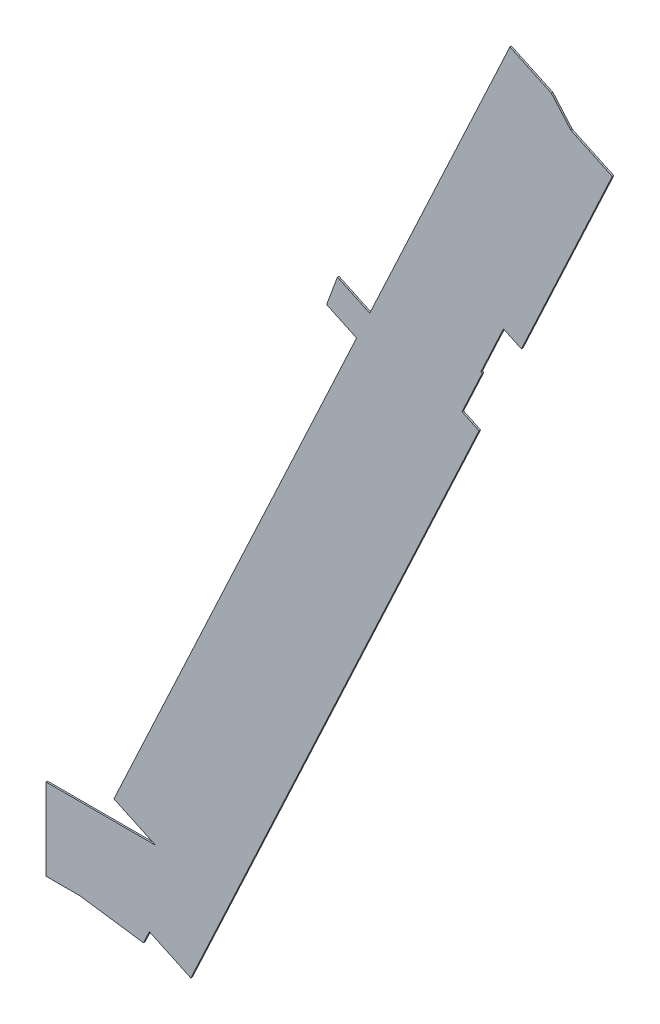
SolidWorks part; units mm, degrees
ref_plane "前视基准面" through (0, 0, 0) normal (0, 0, 1) x (1, 0, 0)
ref_plane "上视基准面" through (0, 0, 0) normal (0, 1, 0) x (1, 0, 0)
ref_plane "右视基准面" through (0, 0, 0) normal (1, 0, 0) x (0, 0, -1)
ref_plane "基准面4"
sketch "草图1" plane through (0, 0, 49.5) normal (0, 0, 1) x (1, 0, 0)
  line L0 (1395.4872, -638.5196) -> (1368.2979, -625.8411)
  line L1 (1368.2979, -625.8411) -> (1364.6212, -633.726)
  line L2 (1364.6212, -633.726) -> (1391.8104, -646.4045)
  line L3 (1391.8104, -646.4045) -> (1395.4872, -638.5196)
  line L4 (1345.9654, -713.9589) -> (1330.5581, -706.7744)
  line L5 (1330.5581, -706.7744) -> (1315.7665, -738.4951)
  line L6 (1315.7665, -738.4951) -> (1331.1737, -745.6797)
  line L7 (1331.1737, -745.6797) -> (1345.9654, -713.9589)
  line L8 (1406.3907, -615.1369) -> (1379.2015, -602.4583)
  line L9 (1379.2015, -602.4583) -> (1368.2979, -625.8411)
  line L10 (1368.2979, -625.8411) -> (1395.4872, -638.5196)
  line L11 (1395.4872, -638.5196) -> (1406.3907, -615.1369)
  line L12 (1176.9999, -1107.779) -> (1149.8106, -1095.1004)
  line L13 (1149.8106, -1095.1004) -> (1135.3148, -1126.1868)
  line L14 (1135.3148, -1126.1868) -> (1162.5041, -1138.8653)
  line L15 (1162.5041, -1138.8653) -> (1176.9999, -1107.779)
  line L16 (1207.7242, -1041.8904) -> (1180.535, -1029.2118)
  line L17 (1180.535, -1029.2118) -> (1165.4053, -1061.6577)
  line L18 (1165.4053, -1061.6577) -> (1192.5945, -1074.3362)
  line L19 (1192.5945, -1074.3362) -> (1207.7242, -1041.8904)
  line L20 (1238.4063, -976.0924) -> (1211.2171, -963.4139)
  line L21 (1211.2171, -963.4139) -> (1195.876, -996.3129)
  line L22 (1195.876, -996.3129) -> (1223.0653, -1008.9914)
  line L23 (1223.0653, -1008.9914) -> (1238.4063, -976.0924)
  line L24 (1223.0653, -1008.9914) -> (1195.876, -996.3129)
  line L25 (1195.876, -996.3129) -> (1180.535, -1029.2118)
  line L26 (1180.535, -1029.2118) -> (1207.7242, -1041.8904)
  line L27 (1207.7242, -1041.8904) -> (1223.0653, -1008.9914)
  line L28 (1192.5945, -1074.3362) -> (1165.4053, -1061.6577)
  line L29 (1165.4053, -1061.6577) -> (1149.8106, -1095.1004)
  line L30 (1149.8106, -1095.1004) -> (1176.9999, -1107.779)
  line L31 (1176.9999, -1107.779) -> (1192.5945, -1074.3362)
  line L32 (1391.8104, -646.4045) -> (1364.6212, -633.726)
  line L33 (1364.6212, -633.726) -> (1347.97, -669.4345)
  line L34 (1347.97, -669.4345) -> (1375.1592, -682.113)
  line L35 (1375.1592, -682.113) -> (1391.8104, -646.4045)
  line L36 (1375.1592, -682.113) -> (1347.97, -669.4345)
  line L37 (1347.97, -669.4345) -> (1330.5581, -706.7744)
  line L38 (1330.5581, -706.7744) -> (1345.9654, -713.9589)
  line L39 (1345.9654, -713.9589) -> (1357.7474, -719.4529)
  line L40 (1357.7474, -719.4529) -> (1375.1592, -682.113)
  line L41 (1113.8458, -1172.2272) -> (1141.0351, -1184.9058)
  line L42 (1141.0351, -1184.9058) -> (1162.5041, -1138.8653)
  line L43 (1162.5041, -1138.8653) -> (1135.3148, -1126.1868)
  line L44 (1135.3148, -1126.1868) -> (1113.8458, -1172.2272)
  line L45 (1305.8562, -831.4457) -> (1278.6669, -818.7672)
  line L46 (1278.6669, -818.7672) -> (1256.564, -866.1671)
  line L47 (1256.564, -866.1671) -> (1283.7532, -878.8456)
  line L48 (1283.7532, -878.8456) -> (1305.8562, -831.4457)
  line L49 (1283.7532, -878.8456) -> (1256.564, -866.1671)
  line L50 (1256.564, -866.1671) -> (1234.2498, -914.0201)
  line L51 (1234.2498, -914.0201) -> (1261.439, -926.6987)
  line L52 (1261.439, -926.6987) -> (1283.7532, -878.8456)
  line L53 (1261.439, -926.6987) -> (1234.2498, -914.0201)
  line L54 (1234.2498, -914.0201) -> (1211.2171, -963.4139)
  line L55 (1211.2171, -963.4139) -> (1238.4063, -976.0924)
  line L56 (1238.4063, -976.0924) -> (1261.439, -926.6987)
  line L57 (1318.7853, -774.6129) -> (1302.7444, -767.1329)
  line L58 (1302.7444, -767.1329) -> (1278.6669, -818.7672)
  line L59 (1278.6669, -818.7672) -> (1305.8562, -831.4457)
  line L60 (1305.8562, -831.4457) -> (1329.9336, -779.8115)
  line L61 (1329.9336, -779.8115) -> (1318.7853, -774.6129)
  line L62 (1226.4, -727) -> (1213.4, -757.7)
  line L63 (1213.4, -757.7) -> (1226.7468, -764.5456)
  line L64 (1226.7468, -764.5456) -> (1230.0392, -758.1265)
  line L65 (1230.0392, -758.1265) -> (1249.6843, -767.2872)
  line L66 (1249.6843, -767.2872) -> (1224.7498, -820.7594)
  line L67 (1224.7498, -820.7594) -> (1213.6349, -844.5953)
  line L68 (1213.6349, -844.5953) -> (1198.4207, -877.2223)
  line L69 (1198.4207, -877.2223) -> (1183.1219, -910.0307)
  line L70 (1183.1219, -910.0307) -> (1170.2743, -937.5824)
  line L71 (1170.2743, -937.5824) -> (1150.6648, -979.6351)
  line L72 (1150.6648, -979.6351) -> (1135.4506, -1012.2622)
  line L73 (1135.4506, -1012.2622) -> (1122.3494, -1040.3577)
  line L74 (1122.3494, -1040.3577) -> (1107.8959, -1071.3535)
  line L75 (1107.8959, -1071.3535) -> (1090.6108, -1108.4215)
  line L76 (1090.6108, -1108.4215) -> (1117.8, -1121.1)
  line L77 (1117.8, -1121.1) -> (1068.2, -1121.1)
  line L78 (1068.2, -1121.1) -> (1046.2, -1121.1)
  line L79 (1046.2, -1121.1) -> (1046.2, -1174.6)
  line L80 (1046.2, -1174.6) -> (1068.2, -1174.6)
  line L81 (1068.2, -1174.6) -> (1110, -1180.4746)
  line L82 (1110, -1180.4746) -> (1113.8458, -1172.2272)
  line L83 (1113.8458, -1172.2272) -> (1135.3148, -1126.1868)
  line L84 (1135.3148, -1126.1868) -> (1149.8106, -1095.1004)
  line L85 (1149.8106, -1095.1004) -> (1165.4053, -1061.6577)
  line L86 (1165.4053, -1061.6577) -> (1180.535, -1029.2118)
  line L87 (1180.535, -1029.2118) -> (1195.876, -996.3129)
  line L88 (1195.876, -996.3129) -> (1211.2171, -963.4139)
  line L89 (1211.2171, -963.4139) -> (1234.2498, -914.0201)
  line L90 (1234.2498, -914.0201) -> (1256.564, -866.1671)
  line L91 (1256.564, -866.1671) -> (1278.6669, -818.7672)
  line L92 (1278.6669, -818.7672) -> (1302.7444, -767.1329)
  line L93 (1302.7444, -767.1329) -> (1318.7853, -774.6129)
  line L94 (1318.7853, -774.6129) -> (1332.08, -746.1023)
  line L95 (1332.08, -746.1023) -> (1331.1737, -745.6797)
  line L96 (1331.1737, -745.6797) -> (1315.7665, -738.4951)
  line L97 (1315.7665, -738.4951) -> (1330.5581, -706.7744)
  line L98 (1330.5581, -706.7744) -> (1347.97, -669.4345)
  line L99 (1347.97, -669.4345) -> (1364.6212, -633.726)
  line L100 (1364.6212, -633.726) -> (1368.2979, -625.8411)
  line L101 (1368.2979, -625.8411) -> (1379.2015, -602.4583)
  line L102 (1379.2015, -602.4583) -> (1390.1051, -579.0756)
  line L103 (1390.1051, -579.0756) -> (1377.3775, -564.4342)
  line L104 (1377.3775, -564.4342) -> (1350.1883, -551.7557)
  line L105 (1350.1883, -551.7557) -> (1325.0425, -605.681)
  line L106 (1325.0425, -605.681) -> (1321.3657, -613.5659)
  line L107 (1321.3657, -613.5659) -> (1304.2497, -650.2714)
  line L108 (1304.2497, -650.2714) -> (1289.458, -681.9921)
  line L109 (1289.458, -681.9921) -> (1274.4973, -714.0754)
  line L110 (1274.4973, -714.0754) -> (1258.2688, -748.8776)
  line L111 (1258.2688, -748.8776) -> (1237.0998, -739.0064)
  line L112 (1237.0998, -739.0064) -> (1239.7468, -733.8456)
  line L113 (1239.7468, -733.8456) -> (1226.4, -727)
  line L114 (1390.1051, -579.0756) -> (1379.2015, -602.4583)
  line L115 (1379.2015, -602.4583) -> (1406.3907, -615.1369)
  line L116 (1406.3907, -615.1369) -> (1417.2943, -591.7542)
  line L117 (1417.2943, -591.7542) -> (1390.1051, -579.0756)
  dimension "D1" = 15
  dimension "D2" = 15
  dimension "D3" = 5.8
  dimension "D4" = 22
  dimension "D5" = 172
  dimension "D6" = 42.2108
  dimension "D7" = 49.6
  dimension "D8" = 107
  dimension "D9" = 9.1
  dimension "D10" = 30
  dimension "D11" = 50.8
  dimension "D12" = 34.3
  dimension "D13" = 36.9
  dimension "D14" = 35.8
  dimension "D15" = 36.3
  dimension "D16" = 36.3
  dimension "D17" = 54.5
  dimension "D18" = 52.8
  dimension "D19" = 52.3
  dimension "D20" = 30
  dimension "D21" = 40.9
  dimension "D22" = 34.2
  dimension "D23" = 31
  dimension "D24" = 36
  dimension "D25" = 46.4
  dimension "D26" = 30.4
  dimension "D27" = 36.2
  dimension "D28" = 36
  dimension "D29" = 26.3
  dimension "D30" = 59
  dimension "D31" = 38.4
  dimension "D32" = 35.4
  dimension "D33" = 35
  dimension "D34" = 40.5
  dimension "D35" = 8.7
  dimension "D36" = 59.5
  dimension "D37" = 30
  dimension "D38" = 90
  dimension "D39" = 19.4
  dimension "D40" = 30
  dimension "D41" = 25.8
  dimension "D42" = 25.8
  dimension "D43" = 8.7
  dimension "D44" = 39.4
  dimension "D45" = 41.2
  dimension "D46" = 17
  dimension "D47" = 35
  dimension "D48" = 1
  dimension "D49" = 150.1
  dimension "D50" = 2.05
  dimension "D51" = 0.3008
  dimension "D52" = 77.7228
  dimension "D53" = 90
  dimension "D54" = 90
  dimension "D55" = 90
  dimension "D56" = 77.7228
  dimension "D57" = 90
  dimension "D58" = 77.7228
  dimension "D59" = 90
  dimension "D60" = 77.7228
  dimension "D61" = 90
  dimension "D62" = 90
  dimension "D63" = 77.7228
  dimension "D64" = 90
  dimension "D65" = 77.7228
  dimension "D66" = 77.7228
  dimension "D67" = 90
  dimension "D68" = 33.6907
  dimension "D69" = 90
  dimension "D70" = 238.5301
  dimension "D71" = 59.4907
  dimension "D72" = 68.1907
  dimension "D73" = 90
  dimension "D74" = 90
  dimension "D75" = 77.7228
  dimension "D76" = 77.7228
  dimension "D77" = 77.7228
  dimension "D78" = 265.797
extrude "拉伸1" add sketch "草图1" against normal blind 1 contours L2 L3 L0 L1 | L6 L7 L4 L5 | L0 L11 L8 L9 | L14 L15 L12 L13 | L18 L19 L16 L17 | L22 L23 L20 L21 | L16 L27 L22 L25 | L12 L31 L18 L29 | L34 L35 L2 L33 | L39 L40 L34 L37 L4 | L14 L44 L41 L42 | L47 L48 L45 L46 | L51 L52 L47 L50 | L20 L56 L51 L54 | L60 L61 L57 L58 L45 | L112 L113 L62 L63 L64 L65 L66 L67 L68 L69 L70 L71 L72 L73 L74 L75 L76 L77 L78 L79 L80 L81 L82 L44 L13 L29 L17 L25 L21 L54 L50 L46 L58 L57 L94 L95 L6 L5 L37 L33 L1 L9 L102 L103 L104 L105 L106 L107 L108 L109 L110 | L116 L117 L102 L8
ref_plane "基准面5"
sketch "草图2" plane through (0, 0, 49.5) normal (0, 0, 1) x (1, 0, 0)
  line L0 (1239.7468, -733.8456) -> (1226.4, -727)
  line L1 (1226.4, -727) -> (1213.4, -757.7)
  line L2 (1213.4, -757.7) -> (1226.7468, -764.5456)
  line L3 (1226.7468, -764.5456) -> (1230.0392, -758.1265)
  line L4 (1230.0392, -758.1265) -> (1237.0998, -739.0064)
  line L5 (1237.0998, -739.0064) -> (1239.7468, -733.8456)
extrude "拉伸2" cut sketch "草图2" against normal blind 2
